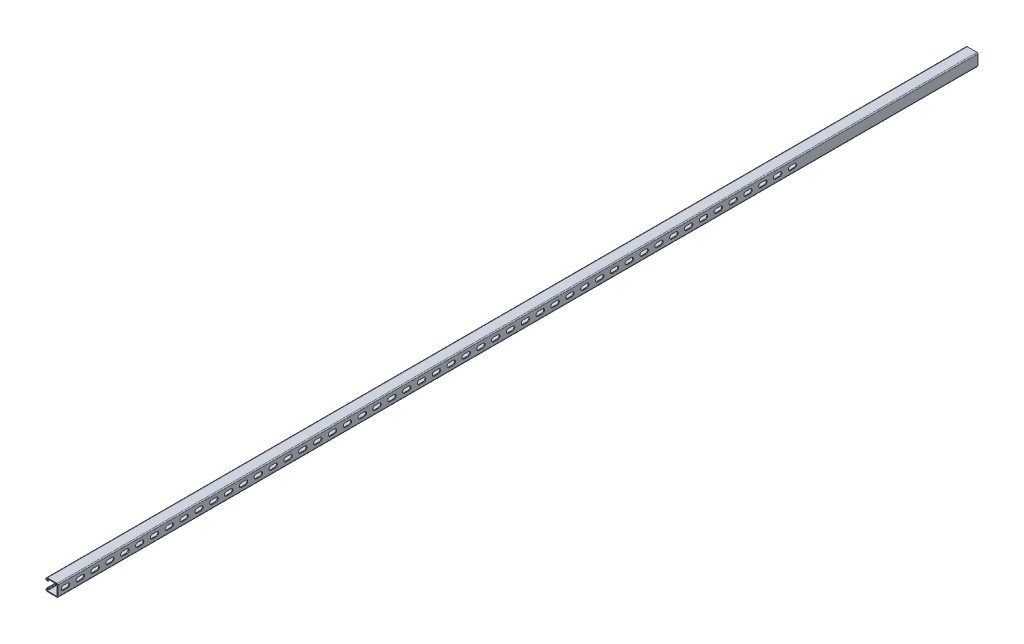
SolidWorks part; units mm, degrees
ref_plane "Front Plane" through (0, 0, 0) normal (0, 0, 1) x (1, 0, 0)
ref_plane "Top Plane" through (0, 0, 0) normal (0, 1, 0) x (1, 0, 0)
ref_plane "Right Plane" through (0, 0, 0) normal (1, 0, 0) x (0, 0, -1)
sketch "Sketch1" plane through (0, 0, 0) normal (0, 0, 1) x (1, 0, 0)
  line L0 (0, 0) -> (-41.275, 0) construction
  line L3 (-41.275, 20.6375) -> (0, 20.6375) construction
  line L4 (-41.275, 20.6375) -> (-41.275, -20.6375) construction
  line L5 (-41.275, -20.6375) -> (0, -20.6375) construction
  line L6 (0, 20.6375) -> (0, -20.6375) construction
  line L7 (-36.2267, 20.6375) -> (-3.4607, 20.6375)
  line L8 (0, 17.1767) -> (0, -17.1767)
  line L9 (-2.794, -17.1767) -> (-2.794, 17.1767)
  line L10 (-3.4608, 17.8435) -> (-36.2267, 17.8435)
  line L11 (-41.275, 15.5892) -> (-41.275, 14.5732)
  line L12 (-37.8142, 11.1125) -> (-35.5346, 11.1125)
  line L14 (-35.5346, 13.9065) -> (-37.8142, 13.9065)
  line L15 (-38.481, 14.5732) -> (-38.481, 15.5892)
  line L16 (-38.481, -14.5733) -> (-38.481, -15.5893)
  line L17 (-35.5346, -13.9065) -> (-37.8142, -13.9065)
  line L18 (-37.8142, -11.1125) -> (-35.5346, -11.1125)
  line L19 (-41.275, -15.5893) -> (-41.275, -14.5733)
  line L20 (-3.4607, -17.8435) -> (-36.2267, -17.8435)
  line L21 (-36.2267, -20.6375) -> (-3.4607, -20.6375)
  line L22 (-2.794, -20.6375) -> (-2.794, 20.6375) construction
  arc A1 (0, 17.1767) -> (-3.4607, 20.6375) centre (-3.4607, 17.1767) ccw
  arc A2 (-2.794, 17.1767) -> (-3.4608, 17.8435) centre (-3.4607, 17.1767) ccw
  arc A4 (-36.2267, 20.6375) -> (-41.275, 15.5892) centre (-36.2267, 15.5892) ccw
  arc A5 (-41.275, 14.5732) -> (-37.8142, 11.1125) centre (-37.8142, 14.5732) ccw
  arc A6 (-35.5346, 11.1125) -> (-35.5346, 13.9065) centre (-35.5346, 12.5095) ccw
  arc A7 (-37.8142, 13.9065) -> (-38.481, 14.5732) centre (-37.8142, 14.5732) cw
  arc A8 (-38.481, 15.5892) -> (-36.2267, 17.8435) centre (-36.2267, 15.5892) cw
  arc A9 (-38.481, -15.5893) -> (-36.2267, -17.8435) centre (-36.2267, -15.5893) ccw
  arc A10 (-37.8142, -13.9065) -> (-38.481, -14.5733) centre (-37.8142, -14.5733) ccw
  arc A11 (-35.5346, -11.1125) -> (-35.5346, -13.9065) centre (-35.5346, -12.5095) cw
  arc A12 (-41.275, -14.5733) -> (-37.8142, -11.1125) centre (-37.8142, -14.5733) cw
  arc A13 (-36.2267, -20.6375) -> (-41.275, -15.5893) centre (-36.2267, -15.5893) cw
  arc A14 (-2.794, -17.1767) -> (-3.4607, -17.8435) centre (-3.4607, -17.1767) cw
  arc A15 (0, -17.1767) -> (-3.4607, -20.6375) centre (-3.4607, -17.1767) cw
  point P24 (0, 20.6375)
  point P65 (-2.794, 0)
  dimension "D1" = 3.4608
  dimension "D2" = 5.0482
  dimension "D3" = 3.4608
  dimension "Ht." = 41.275
  dimension "Wd." = 41.275
  dimension "Thk." = 2.794
  dimension "D4" = 9.525
  dimension "D5" = 7.1374
extrude "Boss-Extrude1" add sketch "Sketch1" against normal blind 2540
sketch "Sketch3" plane through (0, 0, 0) normal (1, 0, 0) x (0, 0, -1)
  line L0 (0, 0) -> (2540, 0) construction
  point P2 (101.6, 0)
  point P3 (2438.4, 0)
  dimension "D1" = 101.6
  dimension "D2" = 101.6
  dimension "D3" = 2540
sketch "Sketch2" plane through (0, 0, 0) normal (1, 0, 0) x (0, 0, -1)
  line L0 (18.2562, 0) -> (32.5437, 0) construction
  line L1 (18.2562, 7.1438) -> (32.5437, 7.1438)
  line L2 (18.2562, -7.1438) -> (32.5437, -7.1438)
  line L3 (18.2562, 0) -> (0, 0) construction
  line L4 (25.4, 0) -> (76.2, 0) construction
  line L5 (0, -17.1767) -> (0, 17.1767) construction
  arc A0 (18.2562, 7.1438) -> (18.2562, -7.1438) centre (18.2562, 0) ccw
  arc A1 (32.5437, -7.1438) -> (32.5437, 7.1438) centre (32.5437, 0) ccw
  point P3 (25.4, 0)
  dimension "Hole to End" = 11.1125
  dimension "D2" = 25.4
extrude "Cut-Extrude1" cut sketch "Sketch2" against normal up to vertex (2.794 mm away) up to point (-2.794, 0, 0)
pattern_linear "LPattern1" count 50 spacing 50.8 along (0, 0, -1) of "Cut-Extrude1"
sketch "Sketch4" plane through (0, 0, -2540) normal (0, 0, -1) x (-1, 0, 0)
  line L14 (36.2267, 20.6375) -> (3.4607, 20.6375)
  line L15 (0, 17.1767) -> (0, -17.1767)
  line L16 (3.4607, -20.6375) -> (36.2267, -20.6375)
  line L17 (41.275, -15.5893) -> (41.275, -14.5733)
  line L18 (37.8142, -11.1125) -> (35.5346, -11.1125)
  line L19 (35.5346, -13.9065) -> (37.8142, -13.9065)
  line L20 (38.481, -14.5733) -> (38.481, -15.5893)
  line L21 (36.2267, -17.8435) -> (3.4607, -17.8435)
  line L22 (2.794, -17.1767) -> (2.794, 17.1767)
  line L23 (3.4608, 17.8435) -> (36.2267, 17.8435)
  line L24 (38.481, 15.5892) -> (38.481, 14.5732)
  line L25 (37.8142, 13.9065) -> (35.5346, 13.9065)
  line L26 (35.5346, 11.1125) -> (37.8142, 11.1125)
  line L27 (41.275, 14.5732) -> (41.275, 15.5892)
  line L28 (36.2267, 20.6375) -> (3.4607, 20.6375)
  line L29 (0, 17.1767) -> (0, -17.1767)
  line L30 (3.4607, -20.6375) -> (36.2267, -20.6375)
  line L31 (41.275, -15.5893) -> (41.275, -14.5733)
  line L32 (37.8142, -11.1125) -> (35.5346, -11.1125)
  line L33 (35.5346, -13.9065) -> (37.8142, -13.9065)
  line L34 (38.481, -14.5733) -> (38.481, -15.5893)
  line L35 (36.2267, -17.8435) -> (3.4607, -17.8435)
  line L36 (2.794, -17.1767) -> (2.794, 17.1767)
  line L37 (3.4608, 17.8435) -> (36.2267, 17.8435)
  line L38 (38.481, 15.5892) -> (38.481, 14.5732)
  line L39 (37.8142, 13.9065) -> (35.5346, 13.9065)
  line L40 (35.5346, 11.1125) -> (37.8142, 11.1125)
  line L41 (41.275, 14.5732) -> (41.275, 15.5892)
  arc A14 (41.275, 15.5892) -> (36.2267, 20.6375) centre (36.2267, 15.5892) ccw
  arc A15 (3.4607, 20.6375) -> (0, 17.1767) centre (3.4607, 17.1767) ccw
  arc A16 (0, -17.1767) -> (3.4607, -20.6375) centre (3.4607, -17.1767) ccw
  arc A17 (36.2267, -20.6375) -> (41.275, -15.5893) centre (36.2267, -15.5893) ccw
  arc A18 (41.275, -14.5733) -> (37.8142, -11.1125) centre (37.8142, -14.5733) ccw
  arc A19 (35.5346, -11.1125) -> (35.5346, -13.9065) centre (35.5346, -12.5095) ccw
  arc A20 (38.481, -14.5733) -> (37.8142, -13.9065) centre (37.8142, -14.5733) ccw
  arc A21 (36.2267, -17.8435) -> (38.481, -15.5893) centre (36.2267, -15.5893) ccw
  arc A22 (2.794, -17.1767) -> (3.4607, -17.8435) centre (3.4607, -17.1767) ccw
  arc A23 (3.4608, 17.8435) -> (2.794, 17.1767) centre (3.4607, 17.1767) ccw
  arc A24 (38.481, 15.5892) -> (36.2267, 17.8435) centre (36.2267, 15.5892) ccw
  arc A25 (37.8142, 13.9065) -> (38.481, 14.5732) centre (37.8142, 14.5732) ccw
  arc A26 (35.5346, 13.9065) -> (35.5346, 11.1125) centre (35.5346, 12.5095) ccw
  arc A27 (37.8142, 11.1125) -> (41.275, 14.5732) centre (37.8142, 14.5732) ccw
  arc A28 (41.275, 15.5892) -> (36.2267, 20.6375) centre (36.2267, 15.5892) ccw
  arc A29 (3.4607, 20.6375) -> (0, 17.1767) centre (3.4607, 17.1767) ccw
  arc A30 (0, -17.1767) -> (3.4607, -20.6375) centre (3.4607, -17.1767) ccw
  arc A31 (36.2267, -20.6375) -> (41.275, -15.5893) centre (36.2267, -15.5893) ccw
  arc A32 (41.275, -14.5733) -> (37.8142, -11.1125) centre (37.8142, -14.5733) ccw
  arc A33 (35.5346, -11.1125) -> (35.5346, -13.9065) centre (35.5346, -12.5095) ccw
  arc A34 (38.481, -14.5733) -> (37.8142, -13.9065) centre (37.8142, -14.5733) ccw
  arc A35 (36.2267, -17.8435) -> (38.481, -15.5893) centre (36.2267, -15.5893) ccw
  arc A36 (2.794, -17.1767) -> (3.4607, -17.8435) centre (3.4607, -17.1767) ccw
  arc A37 (3.4608, 17.8435) -> (2.794, 17.1767) centre (3.4607, 17.1767) ccw
  arc A38 (38.481, 15.5892) -> (36.2267, 17.8435) centre (36.2267, 15.5892) ccw
  arc A39 (37.8142, 13.9065) -> (38.481, 14.5732) centre (37.8142, 14.5732) ccw
  arc A40 (35.5346, 13.9065) -> (35.5346, 11.1125) centre (35.5346, 12.5095) ccw
  arc A41 (37.8142, 11.1125) -> (41.275, 14.5732) centre (37.8142, 14.5732) ccw
  dimension "D1" = 0
extrude "Boss-Extrude2" add sketch "Sketch4" along normal blind 609.6
equation "\"D1@LPattern1\" = \"Slot Ctr.@Sketch2\""
equation "\"Hole Count@LPattern1\" = \"Lg.@Boss-Extrude1\" / \"D1@LPattern1\""
equation "\"D3@Sketch3\" = \"Lg.@Boss-Extrude1\""
